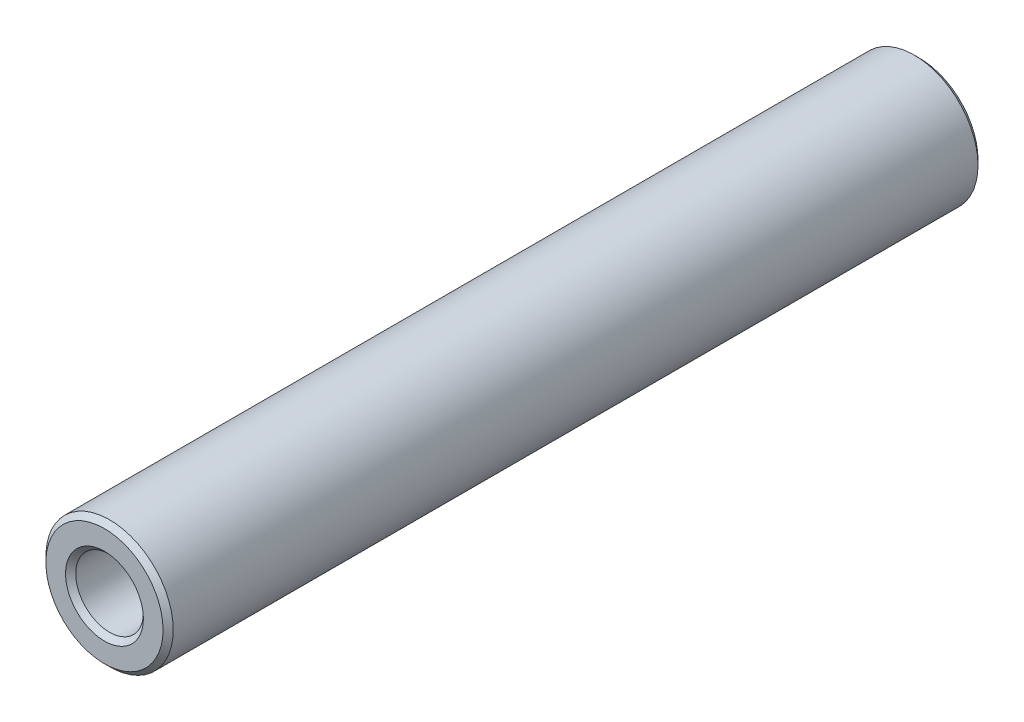
SolidWorks part; units mm, degrees
ref_plane "Front Plane" through (0, 0, 0) normal (0, 0, 1) x (1, 0, 0)
ref_plane "Top Plane" through (0, 0, 0) normal (0, 1, 0) x (1, 0, 0)
ref_plane "Right Plane" through (0, 0, 0) normal (1, 0, 0) x (0, 0, -1)
sketch "Sketch1" plane through (0, 0, 0) normal (0, 0, 1) x (1, 0, 0)
  circle A0 centre (0, 0) radius 3.9688
  circle A1 centre (0, 0) radius 2.1082
  dimension "OD" = 7.9375
  dimension "ID" = 4.2164
sketch "Sketch2" plane through (0, 0, 0) normal (1, 0, 0) x (0, 0, -1)
  line L0 (-25.4, 0) -> (25.4, 0) construction
  point P0 (25.4, 3.9688)
  point P3 (0, 0)
  point P6 (-25.4, 3.9688)
  point P7 (0, 3.9688)
  dimension "Length" = 50.8
sketch "Sketch3" plane through (0, 0, 0) normal (0, 0, 1) x (1, 0, 0)
  circle A0 centre (0, 0) radius 3.9688 construction
  circle A1 centre (0, 0) radius 2.1082 construction
  circle A2 centre (0, 0) radius 3.9688
  circle A3 centre (0, 0) radius 2.1082
extrude "Boss-Extrude1" add sketch "Sketch3" against normal up to vertex (25.4 mm away) and the other way up to vertex (25.4 mm away) up to point (0, 0, -25.4) other way up to point (0, 0, 25.4)
chamfer "Chamfer1" distance 0.3175 angle 45 4 edges at (3.9688, 0, 25.4) (3.9688, 0, -25.4) (2.1082, 0, -25.4) (2.1082, 0, 25.4)
sketch "Sketch4" plane through (0, 0, 0) normal (1, 0, 0) x (0, 0, -1)
  line L0 (25.0825, 2.1082) -> (-25.0825, 2.1082)
  line L1 (-25.0825, -2.1082) -> (25.0825, -2.1082)
  line L2 (-25.0825, -2.1082) -> (25.0825, -2.1082)
  line L3 (25.0825, 2.1082) -> (-25.0825, 2.1082)
equation "\"D1@Chamfer1\"=\"OD@Sketch1\"*.04"
